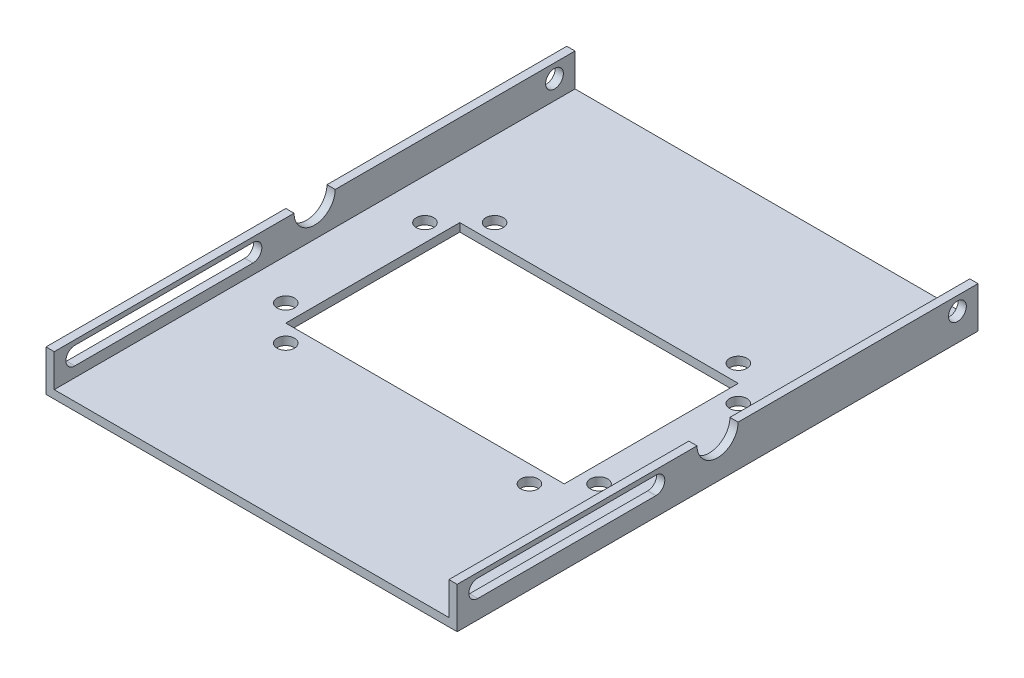
SolidWorks part; units mm, degrees
ref_plane "Front" through (0, 0, 0) normal (0, 0, 1) x (1, 0, 0)
ref_plane "Top" through (0, 0, 0) normal (0, 1, 0) x (1, 0, 0)
ref_plane "Right" through (0, 0, 0) normal (1, 0, 0) x (0, 0, -1)
sketch "Sketch1" plane through (0, 0, 0) normal (0, 0, 1) x (1, 0, 0)
  line L0 (-75, 0) -> (75, 0)
  line L1 (-75, 0) -> (-75, 15)
  line L2 (75, 0) -> (75, 15)
  point P4 (0, 0)
  dimension "D1" = 150
  dimension "D2" = 15
extrude "Extrude-Thin1" add sketch "Sketch1" along normal blind 95 and the other way blind 95 thin thin type one direction reverse wall 3
sketch "Sketch2" plane through (-75, 0, 0) normal (-1, 0, 0) x (0, 0, 1)
  line L0 (-95, 15) -> (95, 15) construction
  line L1 (-95, 15) -> (-95, 0) construction
  line L2 (87.5, 10) -> (22.5, 10) construction
  line L3 (87.5, 6.7615) -> (22.5, 6.7615)
  line L4 (87.5, 13.2385) -> (22.5, 13.2385)
  circle A0 centre (-87.5, 10) radius 3.2385
  arc A1 (87.5, 6.7615) -> (87.5, 13.2385) centre (87.5, 10) ccw
  arc A2 (22.5, 13.2385) -> (22.5, 6.7615) centre (22.5, 10) ccw
  point P8 (55, 10)
  dimension "D1" = 6.477
  dimension "D2" = 5
  dimension "D3" = 7.5
  dimension "D4" = 175
  dimension "D5" = 110
  dimension "D6" = 3.2385
extrude "Cut-Extrude1" cut sketch "Sketch2" against normal through all
sketch "Sketch3" plane through (75, 0, 0) normal (1, 0, 0) x (0, 0, -1)
  line L0 (95, 15) -> (-95, 15) construction
  circle A0 centre (0, 15) radius 7.5
  dimension "D1" = 15
extrude "Cut-Extrude2" cut sketch "Sketch3" against normal through all both and the other way through all
sketch "Sketch4" plane through (0, 3, 0) normal (0, 1, 0) x (1, 0, 0)
  line L1 (-50.8, 31.75) -> (50.8, 31.75)
  line L2 (-50.8, 31.75) -> (-50.8, -31.75)
  line L3 (-50.8, -31.75) -> (50.8, -31.75)
  line L4 (50.8, 31.75) -> (50.8, -31.75)
  line L5 (-50.8, 31.75) -> (50.8, -31.75) construction
  line L6 (-50.8, -31.75) -> (50.8, 31.75) construction
  circle A0 centre (-44.45, 38.1) radius 3.175
  circle A1 centre (44.45, 38.1) radius 3.175
  circle A2 centre (-44.45, -38.1) radius 3.175
  circle A3 centre (44.45, -38.1) radius 3.175
  circle A4 centre (-57.15, 25.4) radius 3.175
  circle A5 centre (57.15, 25.4) radius 3.175
  circle A6 centre (-57.15, -25.4) radius 3.175
  circle A7 centre (57.15, -25.4) radius 3.175
  point P0 (0, 0)
  dimension "D3" = 6.35
  dimension "D1" = 101.6
  dimension "D2" = 63.5
  dimension "D4" = 6.35
  dimension "D5" = 6.35
  dimension "D6" = 6.35
  dimension "D7" = 6.35
  dimension "D8" = 6.35
  dimension "D9" = 6.35
  dimension "D10" = 6.35
  dimension "D11" = 6.35
extrude "Cut-Extrude3" cut sketch "Sketch4" against normal blind 10
